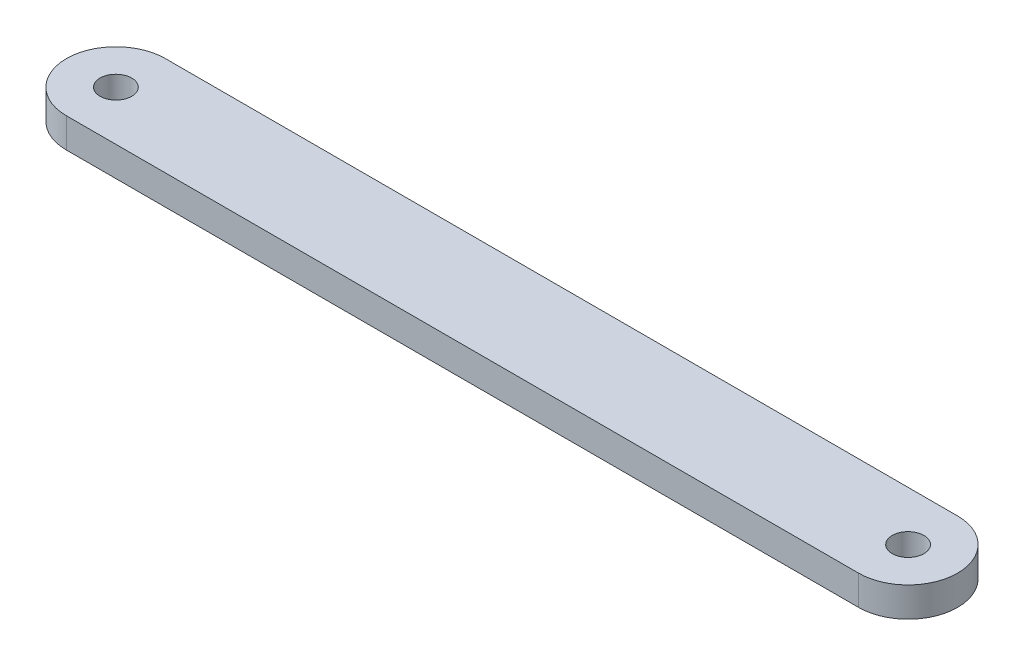
SolidWorks part; units mm, degrees
ref_plane "正面" through (0, 0, 0) normal (0, 0, 1) x (1, 0, 0)
ref_plane "平面" through (0, 0, 0) normal (0, 1, 0) x (1, 0, 0)
ref_plane "右側面" through (0, 0, 0) normal (1, 0, 0) x (0, 0, -1)
sketch "ｽｹｯﾁ1" plane through (0, 0, 0) normal (0, 1, 0) x (1, 0, 0)
  line L0 (0, 0) -> (110, 0) construction
  line L1 (0, -5) -> (80, -5)
  line L3 (0, 5) -> (80, 5)
  circle A0 centre (0, 0) radius 1.6
  circle A1 centre (80, 0) radius 1.6
  arc A2 (0, 5) -> (0, -5) centre (0, 0) ccw
  arc A3 (80, -5) -> (80, 5) centre (80, 0) ccw
  point P1 (0, 0)
  dimension "D5" = 3.2
  dimension "D1" = 5
  dimension "D2" = 10
  dimension "D4" = 80
extrude "ﾎﾞｽ - 押し出し1" add sketch "ｽｹｯﾁ1" along normal blind 3
